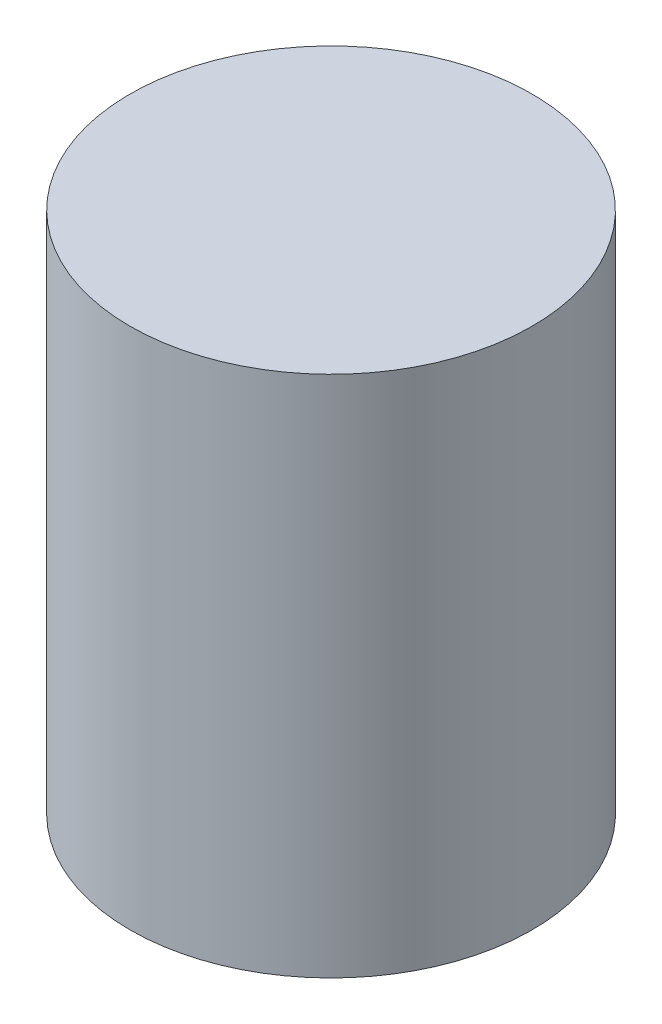
SolidWorks part; units mm, degrees
ref_plane "Front Plane" through (0, 0, 0) normal (0, 0, 1) x (1, 0, 0)
ref_plane "Top Plane" through (0, 0, 0) normal (0, 1, 0) x (1, 0, 0)
ref_plane "Right Plane" through (0, 0, 0) normal (1, 0, 0) x (0, 0, -1)
sketch "Sketch1" plane through (0, 0, 0) normal (0, 1, 0) x (1, 0, 0)
  circle A0 centre (0, 0) radius 12.5
  dimension "D1" = 25
extrude "Boss-Extrude1" add sketch "Sketch1" along normal blind 32.5
